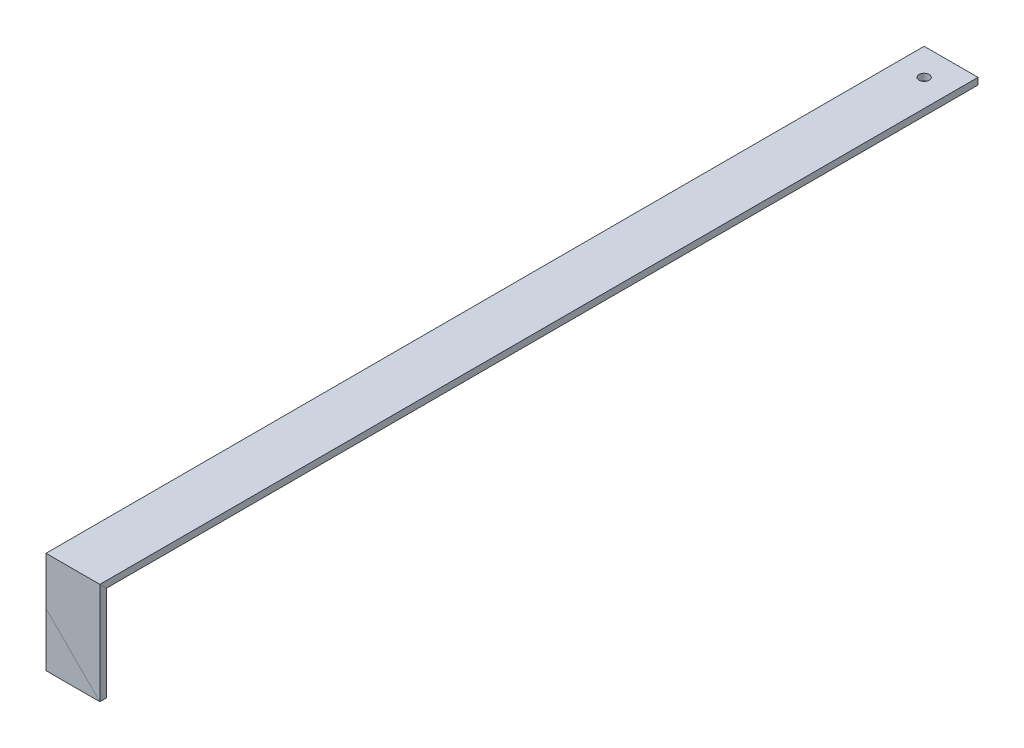
SolidWorks part; units mm, degrees
ref_plane "Alzado" through (0, 0, 0) normal (0, 0, 1) x (1, 0, 0)
ref_plane "Planta" through (0, 0, 0) normal (0, 1, 0) x (1, 0, 0)
ref_plane "Vista lateral" through (0, 0, 0) normal (1, 0, 0) x (0, 0, -1)
sketch "Croquis1" plane through (0, 0, 0) normal (0, 0, 1) x (1, 0, 0)
  line L1 (-25.4, 3.155) -> (25.4, 3.155)
  line L2 (-25.4, 3.155) -> (-25.4, -3.155)
  line L3 (-25.4, -3.155) -> (25.4, -3.155)
  line L4 (25.4, 3.155) -> (25.4, -3.155)
  line L5 (-25.4, 3.155) -> (25.4, -3.155) construction
  line L6 (-25.4, -3.155) -> (25.4, 3.155) construction
  point P0 (0, 0)
  dimension "D1" = 50.8
  dimension "D2" = 6.31
sketch3d "Croquis3D1"
  line L0 (0, 0, 0) -> (0, 0, 891.73)
  line L1 (0, 0, 891.73) -> (0, -67.38, 891.73)
  line L2 (0, -67.38, 891.73) -> (-84.6, -67.38, 891.73)
  dimension "D1" = 891.73
  dimension "D2" = 67.38
  dimension "D3" = 84.6
sweep "Barrer1" add profiles "Croquis1" path "Croquis3D1"
sketch "Croquis2" plane through (0, 3.155, 0) normal (0, 1, 0) x (1, 0, 0)
  line L0 (0, 0) -> (0, -16.5) construction
  line L1 (0, -16.5) -> (0, -47.5) construction
  circle A0 centre (0, -16.5) radius 6.5
  circle A1 centre (0, -47.5) radius 6.5
  dimension "D1" = 13
  dimension "D2" = 13
extrude "Cortar-Extruir1" cut sketch "Croquis2" against normal blind 10
sketch "Croquis3" plane through (0, 0, 846.7461) normal (0, 0, -1) x (-1, 0, 0)
  line L0 (60, -67.3787) -> (63.1123, -64.2664) construction
sketch "Croquis5" plane through (0, 0, 888.575) normal (0, 0, -1) x (-1, 0, 0)
  line L0 (84.6, -92.78) -> (84.6, -41.98) construction
  line L1 (84.6, -41.98) -> (84.6, -67.38) construction
  line L2 (84.6, -67.38) -> (66.5, -67.38) construction
  line L3 (-25.4, -92.78) -> (84.6, -92.78) construction
  circle A0 centre (60, -67.38) radius 6.5
  dimension "D2" = 13
  dimension "D4" = 25.4
  dimension "D1" = 24.6
extrude "Cortar-Extruir4" cut sketch "Croquis5" against normal blind 10
sketch "Croquis7" plane through (0, 0, 888.575) normal (0, 0, -1) x (-1, 0, 0)
  line L0 (25.4, -41.98) -> (25.4, -92.78)
  line L1 (-25.4, -92.78) -> (84.6, -92.78) construction
  line L2 (25.4, -92.78) -> (84.6, -92.78)
  line L3 (84.6, -92.78) -> (84.6, -41.98)
  line L4 (25.4, -41.98) -> (84.6, -41.98)
extrude "Cortar-Extruir5" cut sketch "Croquis7" against normal blind 6.31
sketch "Croquis9" plane through (0, 3.155, 0) normal (0, 1, 0) x (1, 0, 0)
  line L0 (25.4, 0) -> (25.4, -66.2)
  line L1 (25.4, 0) -> (25.4, -894.885) construction
  line L2 (25.4, -66.2) -> (-25.4, -66.2)
  line L3 (-25.4, 0) -> (-25.4, -894.885) construction
  line L4 (-25.4, -66.2) -> (-25.4, 0)
  line L5 (-25.4, 0) -> (25.4, 0)
  dimension "D1" = 66.2
extrude "Cortar-Extruir7" cut sketch "Croquis9" against normal blind 10
sketch "Croquis10" plane through (0, 3.155, 0) normal (0, 1, 0) x (1, 0, 0)
  line L0 (0, -66.2) -> (0, -91.6) construction
  line L1 (-25.4, -66.2) -> (25.4, -66.2) construction
  line L2 (0, -91.6) -> (25.4, -91.6) construction
  circle A0 centre (0, -91.6) radius 4.7625
  dimension "D2" = 9.525
  dimension "D1" = 25.4
extrude "Cortar-Extruir8" cut sketch "Croquis10" against normal blind 10
